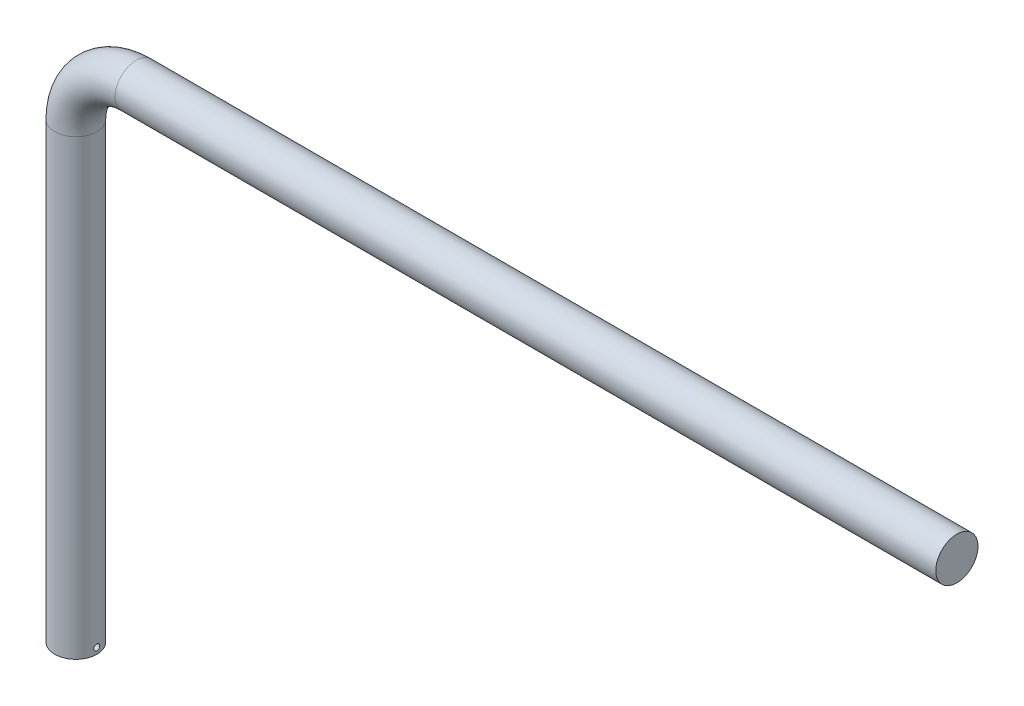
SolidWorks part; units mm, degrees
ref_plane "Front Plane" through (0, 0, 0) normal (0, 0, 1) x (1, 0, 0)
ref_plane "Top Plane" through (0, 0, 0) normal (0, 1, 0) x (1, 0, 0)
ref_plane "Right Plane" through (0, 0, 0) normal (1, 0, 0) x (0, 0, -1)
sketch "Sketch1" plane through (0, 0, 0) normal (0, 0, 1) x (1, 0, 0)
  line L1 (-136, 0) -> (0, 0)
  line L6 (-146, -10) -> (-146, -85)
  arc A0 (-146, -10) -> (-136, 0) centre (-136, -10) cw
  point P7 (-146, 0)
  dimension "D1" = 85
  dimension "D2" = 10
  dimension "D3" = 146
ref_plane "Plane1" through (0, 0, 0) normal (1, 0, 0) x (0, 0, -1)
sketch "Sketch5" plane through (0, 0, 0) normal (1, 0, 0) x (0, 0, -1)
  circle A0 centre (0, 0) radius 3.5
  dimension "D1" = 7
sweep "Sweep1" add profiles "Sketch5" path "Sketch1"
ref_plane "Plane3" through (-150, 0, 0) normal (1, 0, 0) x (0, 0, -1)
sketch "Sketch9" plane through (-150, 0, 0) normal (1, 0, 0) x (0, 0, -1)
  line L0 (0, -85) -> (0, -10) construction
  line L1 (-3.5, -85) -> (3.5, -85) construction
  circle A0 centre (0, -84) radius 0.5
  dimension "D1" = 1
  dimension "D2" = 1
extrude "Cut-Extrude3" cut sketch "Sketch9" against normal through all both and the other way through all
